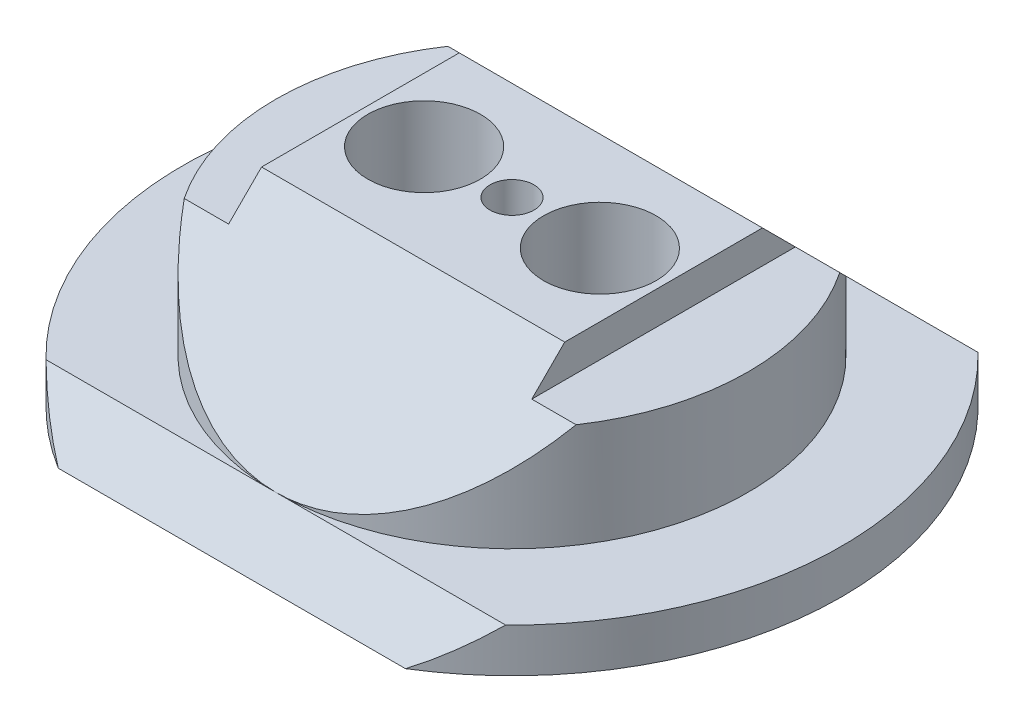
SolidWorks part; units mm, degrees
ref_plane "Front Plane" through (0, 0, 0) normal (0, 0, 1) x (1, 0, 0)
ref_plane "Top Plane" through (0, 0, 0) normal (0, 1, 0) x (1, 0, 0)
ref_plane "Right Plane" through (0, 0, 0) normal (1, 0, 0) x (0, 0, -1)
sketch "Sketch1" plane through (0, 0, 0) normal (0, 1, 0) x (1, 0, 0)
  circle A0 centre (0, 0) radius 30
extrude "Boss-Extrude1" add sketch "Sketch1" along normal blind 4
sketch "Sketch2" plane through (0, 0, 0) normal (1, 0, 0) x (0, 0, -1)
  line L0 (0, 4) -> (21.5, 4)
  line L1 (30, 4) -> (-30, 4) construction
  line L3 (0, 4) -> (-21.5, 4)
  line L5 (0, 4) -> (0, 19.5) construction
  line L6 (-9, 16.5) -> (-21.5, 4)
  line L7 (-9, 16.5) -> (9, 16.5)
  line L9 (9, 16.5) -> (21.5, 4)
  dimension "D1" = 12.5
  dimension "D2" = 45
  dimension "D3" = 21.5
  dimension "D4" = 21.5
  dimension "D5" = 45
sketch "Sketch3" plane through (0, 4, 0) normal (0, 1, 0) x (1, 0, 0)
  circle A0 centre (0, 0) radius 21.5
  dimension "D1" = 43
extrude "Boss-Extrude2" add sketch "Sketch2" along normal up to surface and the other way up to surface up to face at (0, 4, 30) other way up to face at (0, 4, 30)
ref_plane "Plane1" through (0, 12.75, -12.75) normal (0, 0.7071, -0.7071) x (1, 0, 0)
other "SurfaceCut1"
ref_plane "Plane2" through (0, 12.75, 12.75) normal (0, 0.7071, 0.7071) x (1, 0, 0)
other "SurfaceCut2"
extrude "Cut-Extrude2" cut sketch "Sketch3" against normal up to surface (12.5 mm away) flip side to cut contours A0
sketch "Sketch5" plane through (0, 0, 0) normal (0, -1, 0) x (-1, 0, 0)
  line L0 (0, 0) -> (0, -6)
  line L1 (0, -6) -> (-17.5, -6)
  line L2 (-17.5, -6) -> (-17.5, 6)
  line L3 (-17.5, 6) -> (17.5, 6)
  line L4 (17.5, 6) -> (17.5, -6)
  line L5 (17.5, -6) -> (0, -6)
  circle A0 centre (0, 0) radius 6
  circle A1 centre (0, 0) radius 3.5
  dimension "D1" = 12
  dimension "D2" = 7
  dimension "D3" = 12
  dimension "D4" = 6
  dimension "D5" = 35
  dimension "D6" = 17.5
extrude "Boss-Extrude3" add sketch "Sketch5" along normal blind 18 contours L1 L2 L3 L4 L5
sketch "Sketch6" plane through (0, 0, 0) normal (0, -1, 0) x (1, 0, 0)
  line L0 (0, 6) -> (0, 15) construction
  line L1 (-17.5, 6) -> (17.5, 6) construction
  line L2 (0, 15) -> (7, 15)
  line L3 (7, 15) -> (7, 6)
  line L4 (-17.5, 6) -> (17.5, 6) construction
  line L5 (7, 6) -> (-7, 6)
  line L6 (-7, 6) -> (-7, 15)
  line L7 (-7, 15) -> (0, 15)
  dimension "D1" = 14
  dimension "D2" = 9
extrude "Boss-Extrude4" add sketch "Sketch6" along normal blind 15 contours L7 L2 L3 L5 L6
sketch "Sketch7" plane through (0, 0, 0) normal (0, -1, 0) x (1, 0, 0)
  line L0 (0, -6) -> (0, -15) construction
  line L1 (17.5, -6) -> (-17.5, -6) construction
  line L2 (0, -15) -> (7, -15)
  line L3 (7, -15) -> (7, -6)
  line L4 (7, -6) -> (-7, -6)
  line L7 (-7, -6) -> (-7, -15)
  line L8 (-7, -15) -> (0, -15)
  dimension "D1" = 9
  dimension "D2" = 14
extrude "Boss-Extrude5" add sketch "Sketch7" along normal blind 15
sketch "Sketch8" plane through (0, 0, 0) normal (0, 0, 1) x (1, 0, 0)
  line L0 (0, 0) -> (12.5, 0) construction
  line L1 (12.5, 0) -> (12.5, -12.5) construction
  line L2 (12.5, -12.5) -> (-12.5, -12.5) construction
  line L3 (-12.5, -12.5) -> (-12.5, 0) construction
  line L4 (-12.5, 0) -> (0, 0) construction
  circle A0 centre (-12.5, -12.5) radius 2
  circle A1 centre (12.5, -12.5) radius 2
  dimension "D4" = 4
  dimension "D5" = 4
  dimension "D1" = 12.5
  dimension "D2" = 25
  dimension "D3" = 12.5
extrude "Cut-Extrude3" cut sketch "Sketch8" against normal through all both and the other way through all contours A0 | A1
ref_plane "Plane3" through (0, -18, 0) normal (0, -1, 0) x (-1, 0, 0)
ref_plane "Plane4" through (10.366, -9.6749, -8.0624) normal (0.6355, -0.5931, -0.4943) x (-0.3613, 0.3373, -0.8693)
ref_plane "Plane5" through (-10.366, -9.6749, -8.0624) normal (0.6355, 0.5931, 0.4943) x (0.3613, 0.3373, -0.8693)
ref_plane "Plane6" through (10.366, -9.6749, 8.0624) normal (-0.6355, 0.5931, -0.4943) x (-0.3613, 0.3373, 0.8693)
ref_plane "Plane7" through (-10.366, -9.6749, 8.0624) normal (0.6355, 0.5931, -0.4943) x (-0.3613, -0.3373, -0.8693)
ref_plane "Plane9" through (0, 0, 6) normal (0, 0, 1) x (1, 0, 0)
sketch "Sketch16" plane through (0, 0, 6) normal (0, 0, 1) x (1, 0, 0)
  line L0 (17.5, -18) -> (17.5, -14.5)
  line L1 (-6.6, -18) -> (6.6, -18) construction
  line L2 (17.5, -18) -> (17.5, 0) construction
  line L3 (17.5, -18) -> (14, -18)
  line L4 (17.5, -14.5) -> (14, -18)
  line L5 (-17.5, -18) -> (-14, -18)
  line L6 (-17.5, -18) -> (-17.5, 0) construction
  line L7 (-14, -18) -> (-17.5, -14.5)
  line L8 (-17.5, -14.5) -> (-17.5, -18)
  dimension "D2" = 3.5
extrude "Cut-Extrude8" cut sketch "Sketch16" against normal through all both and the other way through all
sketch "Sketch17" plane through (10.366, -9.6749, -8.0624) normal (0.6355, -0.5931, -0.4943) x (-0.3613, 0.3373, -0.8693)
  line L0 (-2.3725, -6.1896) -> (7.9806, -0.7067)
  line L1 (5.4512, -6.1896) -> (10.5101, 4.7762) construction
  line L2 (7.9806, -0.7067) -> (7.9806, -10.9658)
  line L3 (10.5101, -15.7421) -> (5.4512, -6.1896) construction
  line L4 (7.9806, -10.9658) -> (-2.3725, -6.1896)
extrude "Cut-Extrude9" cut sketch "Sketch17" along normal through all
sketch "Sketch19" plane through (-10.366, -9.6749, -8.0624) normal (0.6355, 0.5931, 0.4943) x (0.3613, 0.3373, -0.8693)
  line L0 (-2.3725, -6.1896) -> (7.9806, -10.9658)
  line L1 (7.9806, -10.9658) -> (7.9806, -0.7067)
  line L2 (5.4512, -6.1896) -> (10.5101, 4.7762) construction
  line L3 (7.9806, -0.7067) -> (-2.3725, -6.1896)
extrude "Cut-Extrude11" cut sketch "Sketch19" against normal blind 20 contours L3 L0 L1
sketch "Sketch20" plane through (-10.366, -9.6749, 8.0624) normal (0.6355, 0.5931, -0.4943) x (-0.3613, -0.3373, -0.8693)
  line L0 (2.3725, -6.1896) -> (-7.9806, -0.7067)
  line L1 (-5.4512, -6.1896) -> (-10.5101, 4.7762) construction
  line L2 (-7.9806, -0.7067) -> (-7.9806, -10.9658)
  line L3 (-5.4512, -6.1896) -> (-10.5101, -15.7421) construction
  line L4 (-7.9806, -10.9658) -> (2.3725, -6.1896)
extrude "Cut-Extrude12" cut sketch "Sketch20" against normal blind 20
sketch "Sketch21" plane through (10.366, -9.6749, 8.0624) normal (-0.6355, 0.5931, -0.4943) x (-0.3613, 0.3373, 0.8693)
  line L0 (-2.3725, -6.1896) -> (7.9806, -0.7067)
  line L1 (5.4512, -6.1896) -> (10.5101, 4.7762) construction
  line L2 (7.9806, -0.7067) -> (7.9806, -10.9658)
  line L3 (7.9806, -10.9658) -> (-2.3725, -6.1896)
extrude "Cut-Extrude13" cut sketch "Sketch21" against normal blind 20 contours L0 L2 L3
ref_plane "Plane10" through (0, 16.5, 0) normal (0, 1, 0) x (1, 0, 0)
sketch "Sketch25" plane through (0, 0, 0) normal (0, 0, 1) x (1, 0, 0)
  line L1 (-33.0377, 0) -> (33.0377, 0)
  line L2 (-33.0377, 0) -> (-33.0377, -20.1422)
  line L3 (-33.0377, -20.1422) -> (33.0377, -20.1422)
  line L4 (33.0377, 0) -> (33.0377, -20.1422)
  dimension "D1" = 20.1422
  dimension "D2" = 66.0754
extrude "Cut-Extrude14" cut sketch "Sketch25" along normal through all both and the other way through all
sketch "Sketch26" plane through (0, 16.5, 0) normal (0, 1, 0) x (1, 0, 0)
  line L0 (-9.075, 0) -> (9.075, 0) construction
  circle A0 centre (-8, 0) radius 5.125
  circle A2 centre (8, 0) radius 5.125
  dimension "D1" = 10.25
  dimension "D2" = 10.25
  dimension "D3" = 8
  dimension "D4" = 8
extrude "Cut-Extrude15" cut sketch "Sketch26" against normal blind 24
sketch "Sketch29" plane through (0, 0, 6) normal (0, 0, 1) x (1, 0, 0)
  line L0 (21.5, 4) -> (21.5, 16.5) construction
  line L1 (21.5, 13.5) -> (13.8, 13.5)
  line L2 (21.5, 13.5) -> (21.5, 16.5)
  line L3 (21.5, 16.5) -> (13.8, 16.5)
  line L4 (13.8, 13.5) -> (13.8, 16.5)
  line L5 (9.9, 16.5) -> (-9.9, 16.5) construction
  dimension "D1" = 3
  dimension "D2" = 7.7
extrude "Cut-Extrude17" cut sketch "Sketch29" against normal through all both and the other way through all
sketch "Sketch31" plane through (0, 0, 6) normal (0, 0, 1) x (1, 0, 0)
  line L0 (-21.5, 16.5) -> (-21.5, 4) construction
  line L1 (-21.5, 13.5) -> (-13.8, 13.5)
  line L2 (-21.5, 13.5) -> (-21.5, 16.5)
  line L3 (-21.5, 16.5) -> (-13.8, 16.5)
  line L4 (-13.8, 13.5) -> (-13.8, 16.5)
  line L5 (9.9, 16.5) -> (-9.9, 16.5) construction
  dimension "D1" = 3
  dimension "D2" = 7.7
extrude "Cut-Extrude18" cut sketch "Sketch31" against normal through all both and the other way through all
sketch "Sketch34" plane through (0, 0, 0) normal (0, -1, 0) x (1, 0, 0)
  circle A0 centre (0, 0) radius 1.5
  dimension "D1" = 3
extrude "Cut-Extrude21" cut sketch "Sketch34" against normal blind 20
sketch "Sketch35" plane through (0, 16.5, 0) normal (0, 1, 0) x (1, 0, 0)
  circle A0 centre (0, 0) radius 2
  dimension "D1" = 4
extrude "Cut-Extrude22" cut sketch "Sketch35" against normal blind 3
sketch "Sketch37" plane through (0, 0, 0) normal (0, -1, 0) x (1, 0, 0)
  line L0 (0, -9.075) -> (0, 9.075) construction
  line L1 (9.075, 0) -> (-9.075, 0) construction
  circle A0 centre (0, -15) radius 5
  circle A1 centre (0, 15) radius 5
  circle A2 centre (-22, 0) radius 5
  circle A3 centre (22, 0) radius 5
  circle A4 centre (-14, 12) radius 5
  circle A5 centre (14, 12) radius 5
  circle A6 centre (-14, -12) radius 5
  circle A7 centre (14, -12) radius 5
  dimension "D1" = 10
  dimension "D2" = 10
  dimension "D3" = 10
  dimension "D4" = 10
  dimension "D10" = 10
  dimension "D14" = 10
  dimension "D15" = 10
  dimension "D16" = 10
  dimension "D5" = 15
  dimension "D6" = 15
  dimension "D7" = 22
  dimension "D8" = 22
  dimension "D9" = 14
  dimension "D11" = 12
  dimension "D12" = 12
  dimension "D13" = 14
  dimension "D17" = 12
  dimension "D18" = 14
  dimension "D19" = 14
  dimension "D20" = 12
extrude "Cut-Extrude23" cut sketch "Sketch37" against normal blind 3
